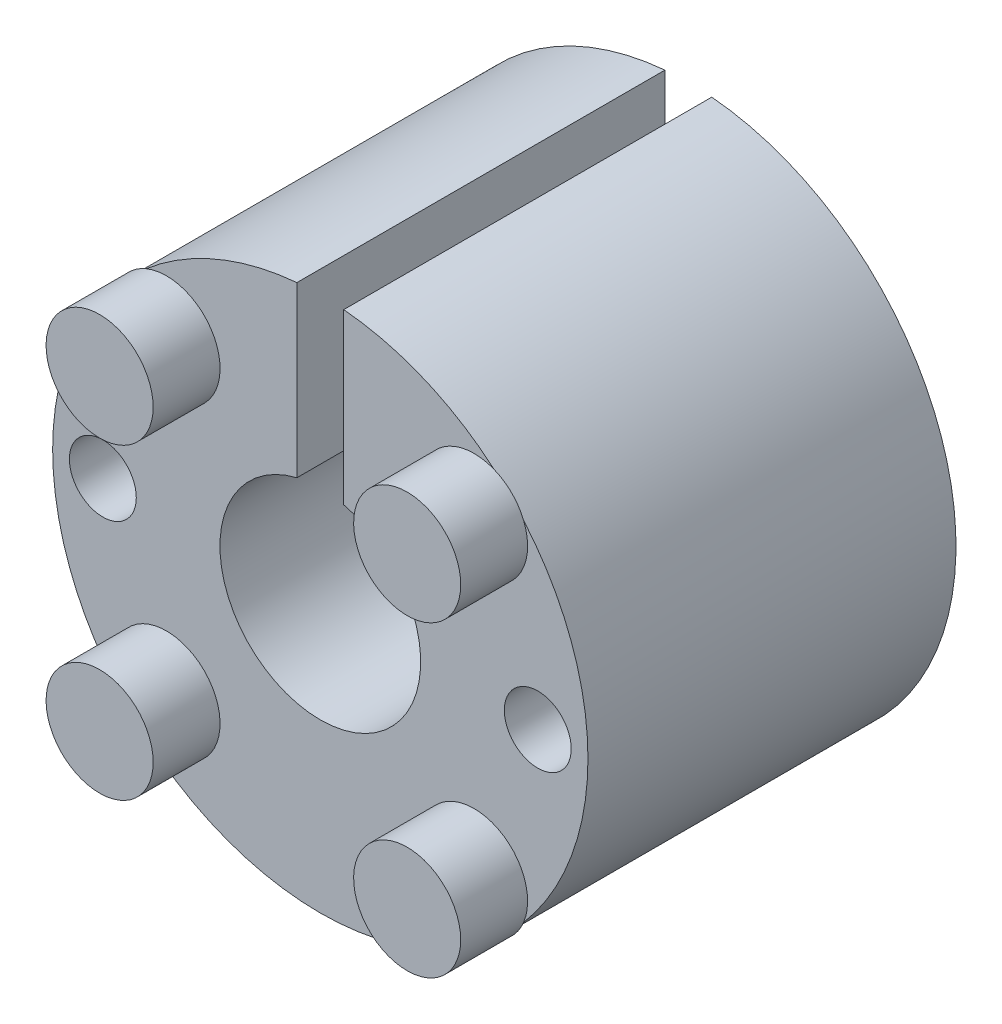
SolidWorks part; units mm, degrees
material "不锈钢 (铁素体)"
ref_plane "前视基准面" through (0, 0, 0) normal (0, 0, 1) x (1, 0, 0)
ref_plane "上视基准面" through (0, 0, 0) normal (0, 1, 0) x (1, 0, 0)
ref_plane "右视基准面" through (0, 0, 0) normal (1, 0, 0) x (0, 0, -1)
sketch "草图1" plane through (0, 0, 0) normal (0, 0, 1) x (1, 0, 0)
  circle A0 centre (0, 0) radius 8
  circle A1 centre (0, 0) radius 3
  dimension "D1" = 16
  dimension "D2" = 6
extrude "凸台-拉伸1" add sketch "草图1" along normal blind 11
sketch "草图2" plane through (0, 0, 11) normal (0, 0, 1) x (1, 0, 0)
  line L1 (-0.7, 9.5427) -> (0.7, 9.5427)
  line L2 (-0.7, 9.5427) -> (-0.7, 2.2133)
  line L3 (-0.7, 2.2133) -> (0.7, 2.2133)
  line L4 (0.7, 9.5427) -> (0.7, 2.2133)
  dimension "D1" = 1.4
  dimension "D2" = 0.7
extrude "切除-拉伸1" cut sketch "草图2" against normal blind 13.5
sketch "草图3" plane through (0, 0, 11) normal (0, 0, 1) x (1, 0, 0)
  circle A0 centre (6.5, 0) radius 1
  circle A1 centre (-6.5, 0) radius 1
  dimension "D3" = 2
  dimension "D4" = 2
  dimension "D1" = 6.5
  dimension "D2" = 6.5
extrude "切除-拉伸2" cut sketch "草图3" against normal blind 3.5
sketch "草图4" plane through (0, 0, 11) normal (0, 0, 1) x (1, 0, 0)
  line L0 (0, 0) -> (3.164, 0) construction
  line L1 (0, 0) -> (4.5962, 4.5962) construction
  circle A0 centre (4.5962, 4.5962) radius 1.6
  circle A1 centre (4.5962, -4.5962) radius 1.6
  circle A2 centre (-4.5962, -4.5962) radius 1.6
  circle A3 centre (-4.5962, 4.5962) radius 1.6
  dimension "D2" = 3.2
  dimension "D1" = 6.5
  dimension "D4" = 45
  dimension "D3" = 4
extrude "凸台-拉伸3" add sketch "草图4" along normal blind 2
